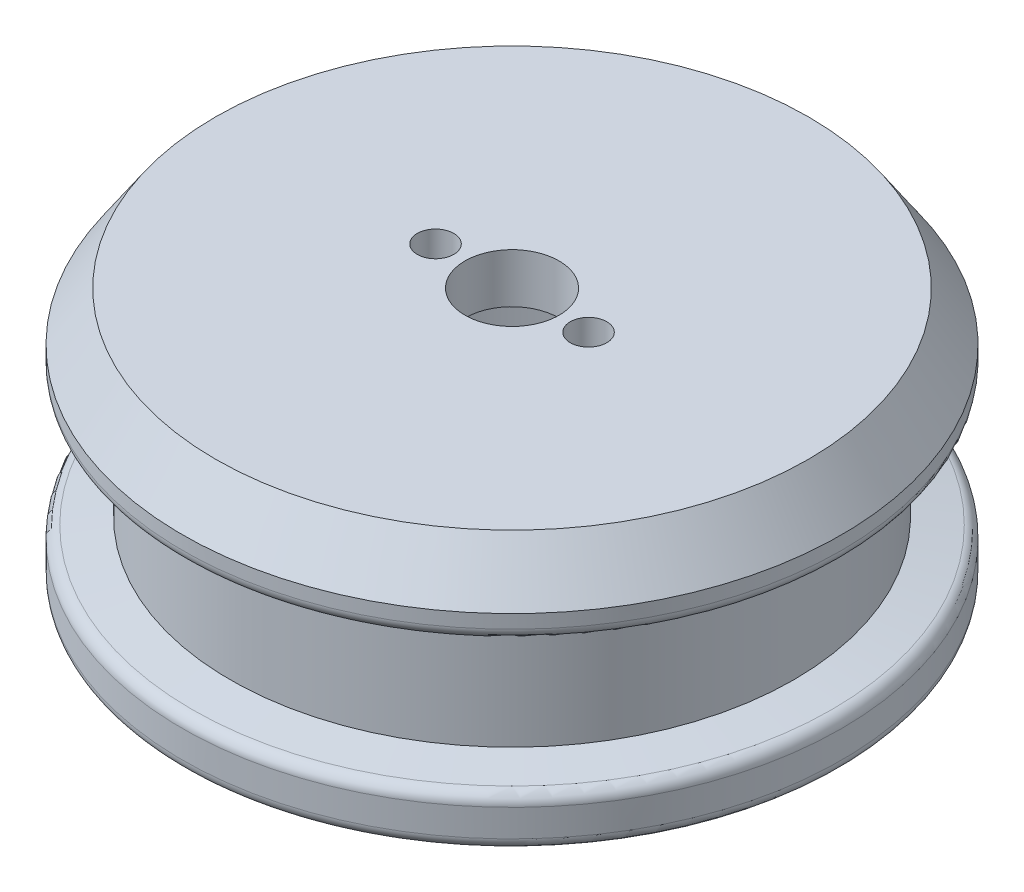
SolidWorks part; units mm, degrees
material "7075-O (SS)"
ref_plane "前视基准面" through (0, 0, 0) normal (0, 0, 1) x (1, 0, 0)
ref_plane "上视基准面" through (0, 0, 0) normal (0, 1, 0) x (1, 0, 0)
ref_plane "右视基准面" through (0, 0, 0) normal (1, 0, 0) x (0, 0, -1)
sketch "草图1" plane through (0, 0, 0) normal (0, 0, 1) x (1, 0, 0)
  line L0 (0, 76.9065) -> (0, -68.6996) construction
  line L1 (28, 36.7209) -> (28, 37.8799)
  line L2 (4, 55.457) -> (4, 51.2569)
  line L3 (4, 51.2569) -> (18.3, 51.2569)
  line L4 (18.3, 51.2569) -> (22, 45.7756)
  line L5 (22, 45.7756) -> (22, 36.7209)
  line L6 (25.1938, 55.457) -> (28, 51.2997)
  line L7 (4, 55.457) -> (25.1938, 55.457)
  line L9 (30.778, 43.5959) -> (27, 43.5959) construction
  line L11 (23.939, 48.5959) -> (23.939, 38.5959)
  line L12 (28, 37.8799) -> (23.939, 38.5959)
  line L13 (28, 49.312) -> (28, 51.2997)
  line L14 (23.939, 43.5959) -> (11.0611, 43.5959) construction
  line L15 (23.939, 48.5959) -> (28, 49.312)
  line L16 (28, 36.7209) -> (28, 33.7209)
  line L18 (22, 33.7209) -> (22, 36.7209)
  line L19 (22, 33.7209) -> (28, 33.7209)
  point P17 (23.939, 43.5959)
  dimension "D1" = 100
  dimension "D5" = 22
  dimension "D6" = 4
  dimension "D7" = 6
revolve "旋转1" add sketch "草图1" angle 360 about L0
sketch "草图3" plane through (0, 55.457, 0) normal (0, 1, 0) x (1, 0, 0)
  line L0 (0, 7.8995) -> (0, -12.6463) construction
  circle A0 centre (-6.5, 0) radius 1.55
  circle A1 centre (6.5, 0) radius 1.55
  dimension "D1" = 6.5
  dimension "D2" = 3.1
extrude "切除-拉伸1" cut sketch "草图3" against normal blind 10
fillet "圆角1" radius 1 1 edges at (-28, 49.312, 0)
fillet "圆角2" radius 1 1 edges at (-28, 37.8799, 0)
fillet "圆角3" radius 1 1 edges at (-28, 33.7209, 0)
